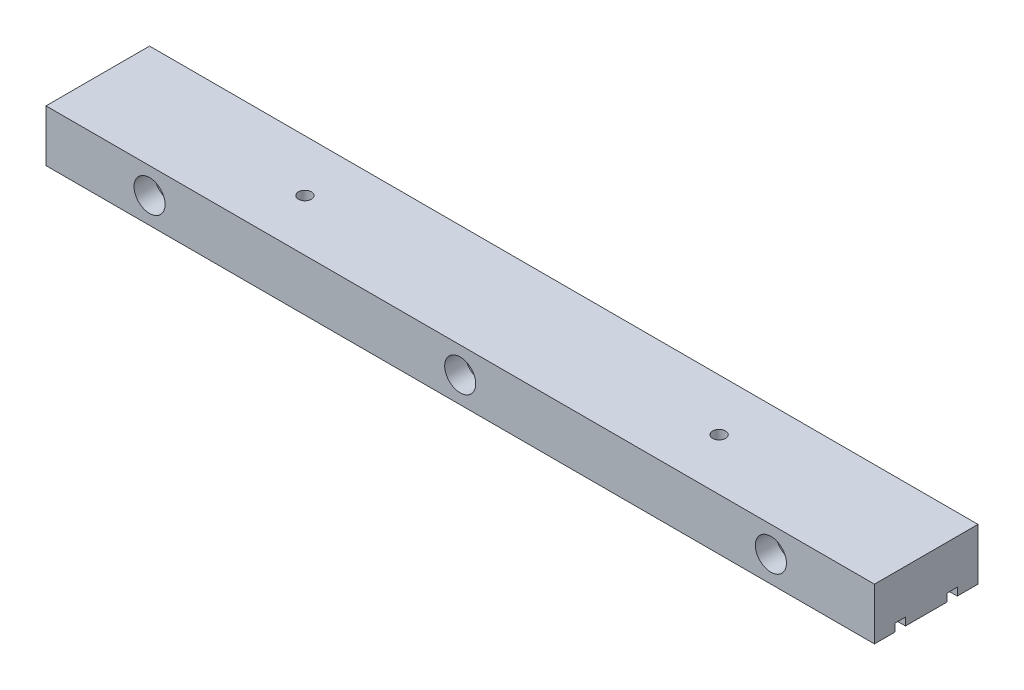
SolidWorks part; units mm, degrees
ref_plane "Ön Düzlem" through (0, 0, 0) normal (0, 0, 1) x (1, 0, 0)
ref_plane "Üst Düzlem" through (0, 0, 0) normal (0, 1, 0) x (1, 0, 0)
ref_plane "Sağ Düzlem" through (0, 0, 0) normal (1, 0, 0) x (0, 0, -1)
sketch "Çizim1" plane through (0, 0, 0) normal (0, 0, 1) x (1, 0, 0)
  line L1 (0, 0) -> (160, 0)
  line L2 (0, 0) -> (0, 10)
  line L3 (0, 10) -> (160, 10)
  line L4 (160, 0) -> (160, 10)
  dimension "D4" = 10
extrude "Yükseklik-Ekstrüzyon1" add sketch "Çizim1" along normal blind 20
sketch "Çizim4" plane through (0, 10, 0) normal (0, 1, 0) x (1, 0, 0)
  line L0 (0, -10) -> (160, -10) construction
  line L1 (0, -20) -> (0, 0) construction
  line L2 (160, -20) -> (160, 0) construction
  line L3 (40, 0) -> (40, -20) construction
  line L4 (160, 0) -> (0, 0) construction
  line L5 (160, -20) -> (0, -20) construction
  line L6 (120, 0) -> (120, -20) construction
  circle A0 centre (40, -10) radius 1.25
  circle A1 centre (120, -10) radius 1.25
  point P16 (40, -10)
  point P17 (120, -10)
  dimension "D1" = 40
  dimension "D2" = 40
sketch "Çizim6" plane through (0, 0, 0) normal (-1, 0, 0) x (0, 0, 1)
  line L0 (20, 0) -> (0, 0) construction
  line L1 (0, 10) -> (0, 0) construction
  line L2 (4, 0) -> (6, 0)
  line L3 (4, 0) -> (4, 1.5)
  line L4 (4, 1.5) -> (6, 1.5)
  line L5 (6, 0) -> (6, 1.5)
  line L6 (14, 0) -> (16, 0)
  line L7 (14, 0) -> (14, 1.5)
  line L8 (14, 1.5) -> (16, 1.5)
  line L9 (16, 0) -> (16, 1.5)
  line L10 (20, 10) -> (20, 0) construction
  dimension "D1" = 4
  dimension "D2" = 4
  dimension "D3" = 2
  dimension "D4" = 2
  dimension "D5" = 1.5
extrude "Kes-Ekstrüzyon1" cut sketch "Çizim6" against normal through all
sketch "Çizim7" plane through (0, 0, 0) normal (0, 0, -1) x (-1, 0, 0)
  line L0 (-160, 5) -> (0, 5) construction
  line L1 (-160, 0) -> (-160, 10) construction
  line L2 (0, 10) -> (0, 0) construction
  circle A0 centre (-140, 5) radius 1.25
  circle A1 centre (-80, 5) radius 1.25
  circle A2 centre (-20, 5) radius 1.25
  point P6 (-140, 5)
  point P7 (-80, 5)
  point P8 (-20, 5)
  point P15 (0, 0)
  dimension "D1" = 20
  dimension "D2" = 20
extrude "Cut-Extrude1" cut sketch "Çizim4" against normal through all
cosmetic thread "Cosmetic Thread1" parameters "D2"=3
cosmetic thread "Cosmetic Thread2" parameters "D2"=3
extrude "Cut-Extrude2" cut sketch "Çizim7" against normal through all
sketch "Sketch1" plane through (0, 0, 0) normal (0, 0, -1) x (-1, 0, 0)
  circle A0 centre (-140, 5) radius 3
  circle A1 centre (-80, 5) radius 3
  circle A2 centre (-20, 5) radius 3
extrude "Cut-Extrude3" cut sketch "Sketch1" against normal blind 4
cosmetic thread "Cosmetic Thread6" parameters "D2"=3
cosmetic thread "Cosmetic Thread7" parameters "D2"=3
cosmetic thread "Cosmetic Thread8" parameters "D2"=3
sketch "Sketch2" plane through (0, 0, 20) normal (0, 0, 1) x (1, 0, 0)
  circle A0 centre (20, 5) radius 3
  circle A1 centre (80, 5) radius 3
  circle A2 centre (140, 5) radius 3
extrude "Cut-Extrude4" cut sketch "Sketch2" against normal blind 4
cosmetic thread "Cosmetic Thread3" parameters "D2"=3
cosmetic thread "Cosmetic Thread4" parameters "D2"=3
cosmetic thread "Cosmetic Thread5" parameters "D2"=3
